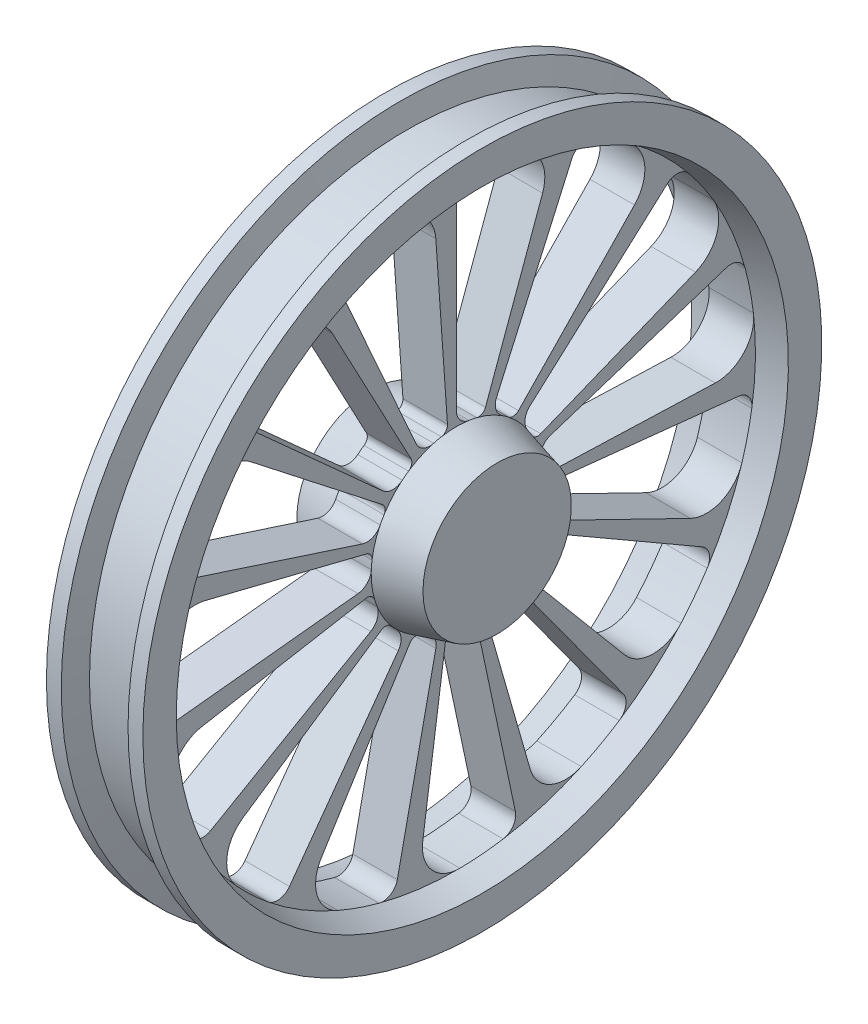
SolidWorks part; units mm, degrees
material "1060 Alloy"
ref_plane "Front Plane" through (0, 0, 0) normal (0, 0, 1) x (1, 0, 0)
ref_plane "Top Plane" through (0, 0, 0) normal (0, 1, 0) x (1, 0, 0)
ref_plane "Right Plane" through (0, 0, 0) normal (1, 0, 0) x (0, 0, -1)
sketch "Sketch1" plane through (0, 0, 0) normal (0, 0, 1) x (1, 0, 0)
  line L0 (0, 0) -> (0, 100)
  line L1 (0, 100) -> (55, 114.7372)
  line L2 (55, 114.7372) -> (55, 403.1218)
  line L3 (55, 403.1218) -> (20, 412.5)
  line L4 (20, 412.5) -> (20, 457.5)
  line L5 (20, 457.5) -> (40, 457.5)
  line L6 (40, 457.5) -> (48.0385, 427.5)
  line L7 (48.0385, 427.5) -> (121.9615, 427.5)
  line L8 (0, 0) -> (170, 0) construction
  line L9 (85, 0) -> (85, 427.5) construction
  line L10 (55, 114.7372) -> (0, 114.7372) construction
  line L11 (0, 114.7372) -> (0, 100) construction
  line L12 (55, 403.1218) -> (20, 403.1218) construction
  line L13 (20, 412.5) -> (20, 403.1218) construction
  line L14 (150, 412.5) -> (150, 403.1218) construction
  line L15 (115, 403.1218) -> (150, 403.1218) construction
  line L16 (170, 114.7372) -> (170, 100) construction
  line L17 (115, 114.7372) -> (170, 114.7372) construction
  line L18 (130, 457.5) -> (121.9615, 427.5)
  line L19 (150, 457.5) -> (130, 457.5)
  line L20 (150, 412.5) -> (150, 457.5)
  line L21 (115, 403.1218) -> (150, 412.5)
  line L22 (115, 114.7372) -> (115, 403.1218)
  line L23 (170, 100) -> (115, 114.7372)
  line L24 (170, 0) -> (170, 100)
  line L25 (0, 0) -> (170, 0)
  dimension "D1" = 15
  dimension "D2" = 15
  dimension "D3" = 200
  dimension "D4" = 915
  dimension "D5" = 45
  dimension "D6" = 30
  dimension "D7" = 20
  dimension "D8" = 30
  dimension "D9" = 130
  dimension "D10" = 170
revolve "Revolve1" add sketch "Sketch1" angle 360 about L25
sketch "Sketch2" plane through (115, 0, 0) normal (1, 0, 0) x (0, 0, -1)
  line L0 (0, 133.2446) -> (0, 382.5994)
  line L1 (39.2638, 117.6886) -> (116.2346, 329.164)
  circle A0 centre (0, 0) radius 114.7372 construction
  circle A1 centre (0, 0) radius 403.1218 construction
  arc A2 (21.0441, 402.5721) -> (79.0553, 395.2941) centre (0, 0) cw
  arc A3 (17.0313, 113.4661) -> (27.4725, 111.3997) centre (0, 0) cw
  arc A4 (0, 382.5994) -> (21.0441, 402.5721) centre (20, 382.5994) cw
  arc A5 (116.2346, 329.164) -> (79.0553, 395.2941) centre (69.2499, 346.265) ccw
  arc A6 (0, 133.2446) -> (17.0313, 113.4661) centre (20, 133.2446) ccw
  arc A7 (39.2638, 117.6886) -> (27.4725, 111.3997) centre (29.8669, 121.1088) cw
  point P13 (0, 403.1218)
  point P16 (134.7174, 379.9452)
  point P19 (0, 114.7372)
  point P22 (36.0721, 108.9194)
  dimension "D2" = 20
  dimension "D3" = 50
  dimension "D4" = 20
  dimension "D5" = 10
  dimension "D6" = 114.7372
  dimension "D7" = 403.1218
  dimension "D1" = 20
  dimension "D8" = 225.0474
extrude "Cut-Extrude1" cut sketch "Sketch2" against normal through all
pattern_circular "CirPattern1" count 15 over 360 about axis through (0, 0, 0) along (1, 0, 0) of "Cut-Extrude1"
equation "\"A\"= 130"
equation "\"B\"= 915"
